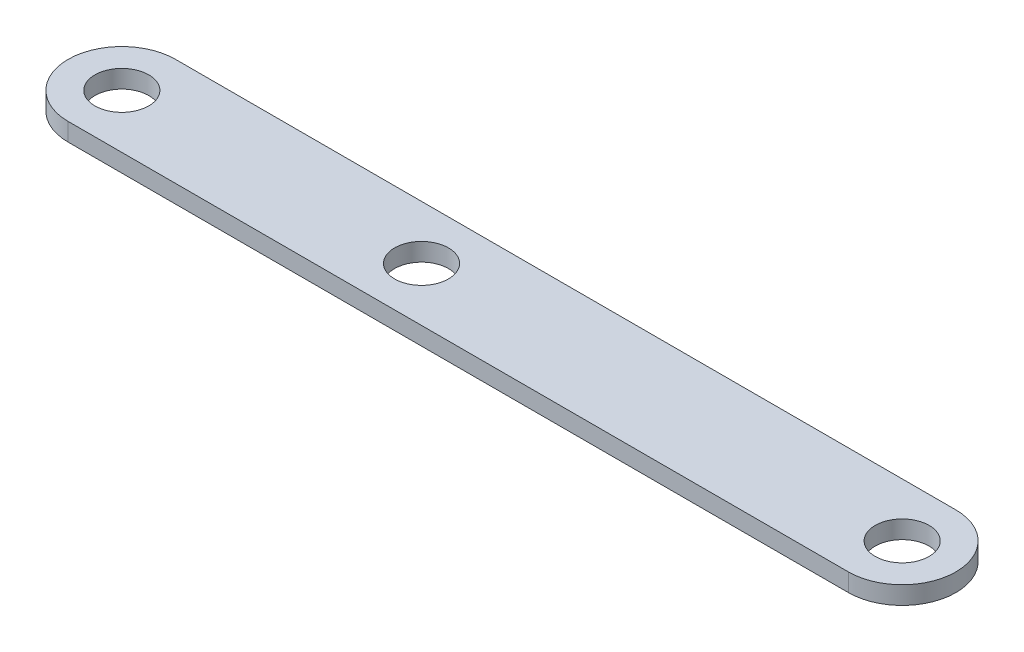
SolidWorks part; units mm, degrees
ref_plane "Front Plane" through (0, 0, 0) normal (0, 0, 1) x (1, 0, 0)
ref_plane "Top Plane" through (0, 0, 0) normal (0, 1, 0) x (1, 0, 0)
ref_plane "Right Plane" through (0, 0, 0) normal (1, 0, 0) x (0, 0, -1)
sketch "Sketch1" plane through (0, 0, 0) normal (0, 1, 0) x (1, 0, 0)
  line L0 (69, 0) -> (69, 16.8638) construction
  line L1 (0, 0) -> (138, 0)
  line L3 (0, 19) -> (138, 19)
  arc A0 (0, 19) -> (0, 0) centre (0, 9.5) ccw
  arc A1 (138, 0) -> (138, 19) centre (138, 9.5) ccw
  circle A2 centre (0, 9.5) radius 4.7625
  circle A3 centre (138, 9.5) radius 4.7625
  circle A5 centre (53, 9.5) radius 4.7625
  dimension "D1" = 9.5
  dimension "D3" = 9.525
  dimension "D2" = 85
  dimension "D4" = 53
extrude "Boss-Extrude1" add sketch "Sketch1" along normal blind 3.175
sketch "Sketch2" plane through (0, 3.175, 0) normal (0, 1, 0) x (1, 0, 0)
  line L2 (138, 19) -> (0, 19) construction
  line L3 (104.7693, 19) -> (128.1255, 19)
  arc A2 (113.4474, 10.3219) -> (119.4474, 10.3219) centre (116.4474, 10.3219) ccw
  arc A3 (113.4474, 10.3219) -> (104.7693, 19) centre (104.7693, 10.3219) ccw
  arc A4 (119.4474, 10.3219) -> (128.1255, 19) centre (128.1255, 10.3219) cw
  dimension "D2" = 3
extrude "Cut-Extrude1" [suppressed] cut sketch "Sketch2" against normal blind 10
